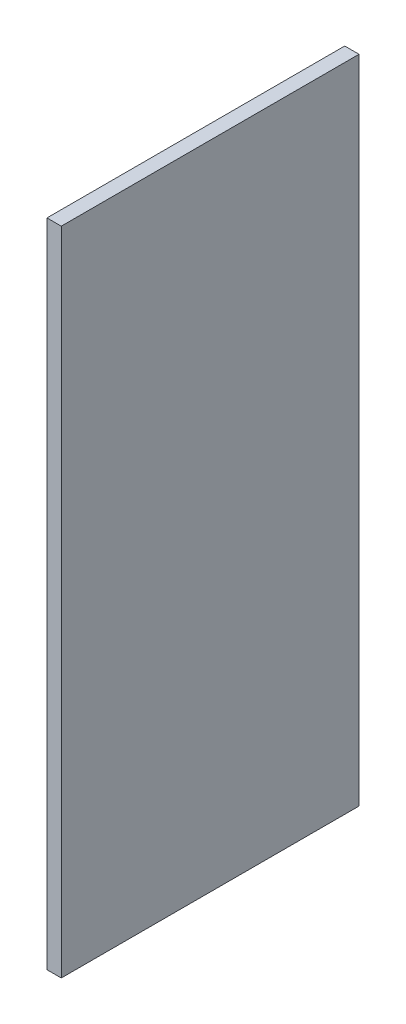
SolidWorks part; units mm, degrees
ref_plane "Alzado" through (0, 0, 0) normal (0, 0, 1) x (1, 0, 0)
ref_plane "Planta" through (0, 0, 0) normal (0, 1, 0) x (1, 0, 0)
ref_plane "Vista lateral" through (0, 0, 0) normal (1, 0, 0) x (0, 0, -1)
ref_plane "Plano_ParedGrandeEste" through (0, 50, 0) normal (0, 1, 0) x (1, 0, 0)
sketch "SkParedGrandeEste" plane through (0, 50, 0) normal (0, 1, 0) x (1, 0, 0)
  line L1 (185, -187.5) -> (203, -187.5)
  line L2 (185, -187.5) -> (185, 187.5)
  line L3 (185, 187.5) -> (203, 187.5)
  line L4 (203, -187.5) -> (203, 187.5)
extrude "ParedGrandeEste" add sketch "SkParedGrandeEste" along normal blind 820 separate body
